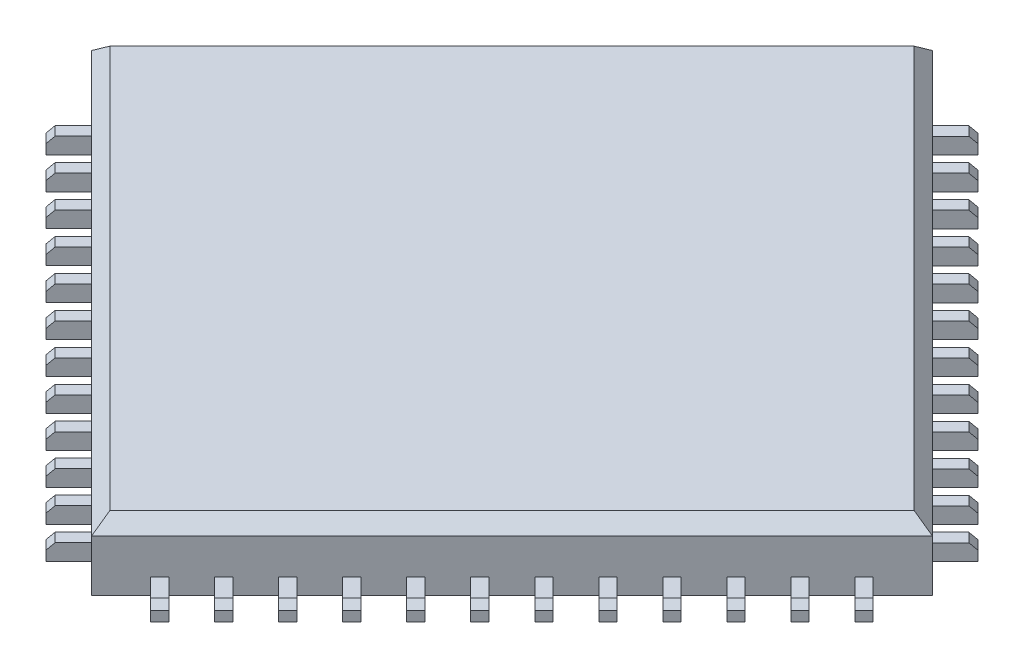
SolidWorks part; units mm, degrees
material "硅"
ref_plane "前视基准面" through (0, 0, 0) normal (0, 0, 1) x (1, 0, 0)
ref_plane "上视基准面" through (0, 0, 0) normal (0, 1, 0) x (1, 0, 0)
ref_plane "右视基准面" through (0, 0, 0) normal (1, 0, 0) x (0, 0, -1)
sketch "草图1" plane through (0, 0, 0) normal (0, 1, 0) x (1, 0, 0)
  line L1 (13, 0) -> (0, 13)
  line L2 (0, 13) -> (-13, 0)
  line L3 (-13, 0) -> (0, -13)
  line L4 (0, -13) -> (13, 0)
  circle A0 centre (0, 0) radius 9.1924 construction
  dimension "D1" = 26
extrude "凸台-拉伸1" add sketch "草图1" along normal blind 2
chamfer "倒角1" distance 0.4 angle 45 4 edges at (-6.5, 2, -6.5) (6.5, 2, -6.5) (6.5, 2, 6.5) (-6.5, 2, 6.5)
sketch "草图3" plane through (-6.5, 0, 6.5) normal (-0.7071, 0, 0.7071) x (0.7071, 0, 0.7071)
  line L0 (-9.1924, 0) -> (9.1924, 0) construction
  line L1 (-7.9024, 0.5) -> (-7.5024, 0.5)
  line L2 (-7.9024, 0.5) -> (-7.9024, 0)
  line L3 (-7.9024, 0) -> (-7.5024, 0)
  line L4 (-7.5024, 0.5) -> (-7.5024, 0)
  line L5 (-9.1924, 1.6) -> (-9.1924, 0) construction
  line L6 (-6.5024, 0.5) -> (-6.5024, 0)
  line L7 (-6.5024, 0) -> (-6.1024, 0)
  line L8 (-6.1024, 0.5) -> (-6.1024, 0)
  line L9 (-6.5024, 0.5) -> (-6.1024, 0.5)
  line L10 (-5.1024, 0.5) -> (-5.1024, 0)
  line L11 (-5.1024, 0) -> (-4.7024, 0)
  line L12 (-4.7024, 0.5) -> (-4.7024, 0)
  line L13 (-5.1024, 0.5) -> (-4.7024, 0.5)
  line L14 (-3.7024, 0.5) -> (-3.7024, 0)
  line L15 (-3.7024, 0) -> (-3.3024, 0)
  line L16 (-3.3024, 0.5) -> (-3.3024, 0)
  line L17 (-3.7024, 0.5) -> (-3.3024, 0.5)
  line L18 (-2.3024, 0.5) -> (-2.3024, 0)
  line L19 (-2.3024, 0) -> (-1.9024, 0)
  line L20 (-1.9024, 0.5) -> (-1.9024, 0)
  line L21 (-2.3024, 0.5) -> (-1.9024, 0.5)
  line L22 (-0.9024, 0.5) -> (-0.9024, 0)
  line L23 (-0.9024, 0) -> (-0.5024, 0)
  line L24 (-0.5024, 0.5) -> (-0.5024, 0)
  line L25 (-0.9024, 0.5) -> (-0.5024, 0.5)
  line L26 (0.4976, 0.5) -> (0.4976, 0)
  line L27 (0.4976, 0) -> (0.8976, 0)
  line L28 (0.8976, 0.5) -> (0.8976, 0)
  line L29 (0.4976, 0.5) -> (0.8976, 0.5)
  line L30 (1.8976, 0.5) -> (1.8976, 0)
  line L31 (1.8976, 0) -> (2.2976, 0)
  line L32 (2.2976, 0.5) -> (2.2976, 0)
  line L33 (1.8976, 0.5) -> (2.2976, 0.5)
  line L34 (3.2976, 0.5) -> (3.2976, 0)
  line L35 (3.2976, 0) -> (3.6976, 0)
  line L36 (3.6976, 0.5) -> (3.6976, 0)
  line L37 (3.2976, 0.5) -> (3.6976, 0.5)
  line L38 (4.6976, 0.5) -> (4.6976, 0)
  line L39 (4.6976, 0) -> (5.0976, 0)
  line L40 (5.0976, 0.5) -> (5.0976, 0)
  line L41 (4.6976, 0.5) -> (5.0976, 0.5)
  line L42 (6.0976, 0.5) -> (6.0976, 0)
  line L43 (6.0976, 0) -> (6.4976, 0)
  line L44 (6.4976, 0.5) -> (6.4976, 0)
  line L45 (6.0976, 0.5) -> (6.4976, 0.5)
  line L46 (7.4976, 0.5) -> (7.4976, 0)
  line L47 (7.4976, 0) -> (7.8976, 0)
  line L48 (7.8976, 0.5) -> (7.8976, 0)
  line L49 (7.4976, 0.5) -> (7.8976, 0.5)
  dimension "D1" = 0.4
  dimension "D2" = 0.5
  dimension "D3" = 1.29
  dimension "D4" = 12
extrude "凸台-拉伸2" add sketch "草图3" along normal blind 1
chamfer "倒角2" distance 0.2 angle 45 12 edges at (-1.7641, 0.5, 12.6501) (-2.754, 0.5, 11.6602) (-3.744, 0.5, 10.6702) (-4.7339, 0.5, 9.6803) (-5.7239, 0.5, 8.6903) (-6.7138, 0.5, 7.7004) (-7.7038, 0.5, 6.7104) (-8.6937, 0.5, 5.7205) (-9.6837, 0.5, 4.7305) (-10.6736, 0.5, 3.7406) (-11.6636, 0.5, 2.7506) (-12.6535, 0.5, 1.7607)
sketch "草图4" plane through (0, 0, 0) normal (0, 0, 1) x (1, 0, 0)
  line L0 (0, 3.9979) -> (0, -2.2016) construction
pattern_circular "阵列(圆周)1" count 4 over 360 about axis through (0, 0, 0) along (0, 1, 0) of "凸台-拉伸2", "倒角2"
